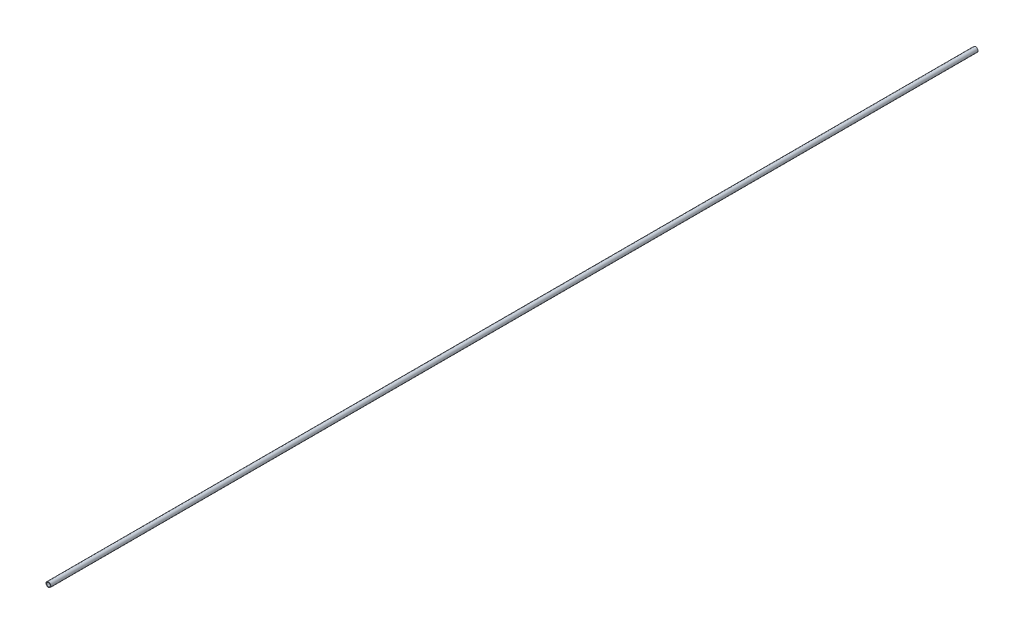
SolidWorks part; units mm, degrees
ref_plane "Front Plane" through (0, 0, 0) normal (0, 0, 1) x (1, 0, 0)
ref_plane "Top Plane" through (0, 0, 0) normal (0, 1, 0) x (1, 0, 0)
ref_plane "Right Plane" through (0, 0, 0) normal (1, 0, 0) x (0, 0, -1)
sketch "Sketch1" plane through (0, 0, 0) normal (0, 0, 1) x (1, 0, 0)
  line L0 (-2.3813, 0) -> (0, 0) construction
  circle A0 centre (0, 0) radius 2.3813
  circle A1 centre (0, 0) radius 1.8288
  point P5 (-1.8288, 0)
  point P6 (-2.3813, 0)
  dimension "ID" = 3.6576
  dimension "OD" = 4.7625
  dimension "Wall Thickness" = 0.5525
sketch "Sketch2" plane through (0, 0, 0) normal (1, 0, 0) x (0, 0, -1)
  line L0 (-457.2, 0) -> (457.2, 0) construction
  line L1 (0, 2.3813) -> (0, -2.3813) construction
  line L2 (0, 2.3813) -> (0, -2.3813) construction
  point P4 (0, 0)
  point P7 (451.2469, 0)
  point P8 (-451.2469, 0)
  dimension "D1" = 5.9531
  dimension "Length" = 914.4
sketch "Sketch3" plane through (0, 0, 0) normal (0, 0, 1) x (1, 0, 0)
  circle A1 centre (0, 0) radius 1.8288
  circle A2 centre (0, 0) radius 1.8288
  circle A3 centre (0, 0) radius 2.3813
  circle A4 centre (0, 0) radius 2.3813
  dimension "D1" = 0
  dimension "D2" = 0
extrude "Boss-Extrude1" add sketch "Sketch3" along normal mid plane 914.4
equation "\"D1@Sketch2\"=\"OD@Sketch1\"*1.25"
equation "\"D1@Boss-Extrude1\"=\"Length@Sketch2\""
